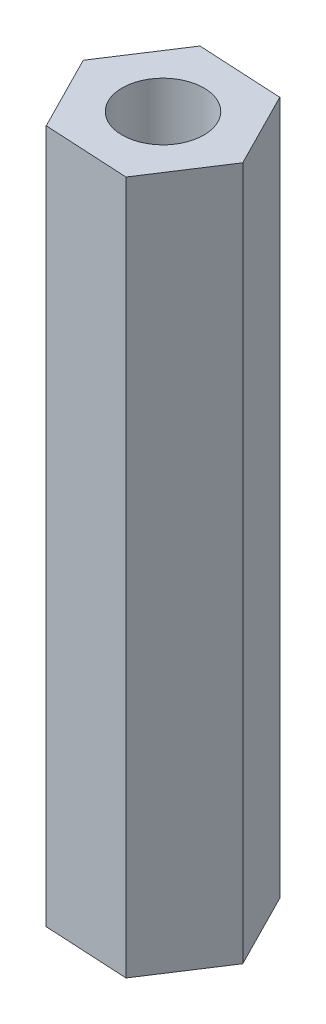
SolidWorks part; units mm, degrees
ref_plane "前视基准面" through (0, 0, 0) normal (0, 0, 1) x (1, 0, 0)
ref_plane "上视基准面" through (0, 0, 0) normal (0, 1, 0) x (1, 0, 0)
ref_plane "右视基准面" through (0, 0, 0) normal (1, 0, 0) x (0, 0, -1)
other "Configuration Table"
sketch "草图1" plane through (0, 0, 0) normal (0, 1, 0) x (1, 0, 0)
  line L1 (3.4015, -0.1819) -> (1.8583, 2.8548)
  line L2 (1.8583, 2.8548) -> (-1.5432, 3.0368)
  line L3 (-1.5432, 3.0368) -> (-3.4015, 0.1819)
  line L4 (-3.4015, 0.1819) -> (-1.8583, -2.8548)
  line L5 (-1.8583, -2.8548) -> (1.5432, -3.0368)
  line L6 (1.5432, -3.0368) -> (3.4015, -0.1819)
  circle A0 centre (0, 0) radius 2.95 construction
  dimension "D1" = 5.9
extrude "凸台-拉伸1" add sketch "草图1" along normal blind 28
hole_wizard "M4 螺纹孔1" positions "草图2" profile "草图3" tap size "M4" standard "GB" end condition through all
sketch "草图2" plane through (0, 28, 0) normal (0, 1, 0) x (1, 0, 0)
  point P0 (0, 0)
sketch "草图3" plane through (0, 28, 0) normal (1, 0, 0) x (0, 0, 1)
  line L0 (0, 0) -> (0, 28)
  line L1 (0, 28) -> (1.65, 28)
  line L2 (1.65, 28) -> (1.65, 0)
  line L5 (1.65, 0) -> (0, 0)
  line L11 (0, -6.35) -> (0, 107.95) construction
  dimension "通孔螺纹孔钻头直径" = 3.3
  dimension "通孔螺纹孔钻头深度" = 28
cosmetic thread "孔螺纹线1" parameters "D2"=4
